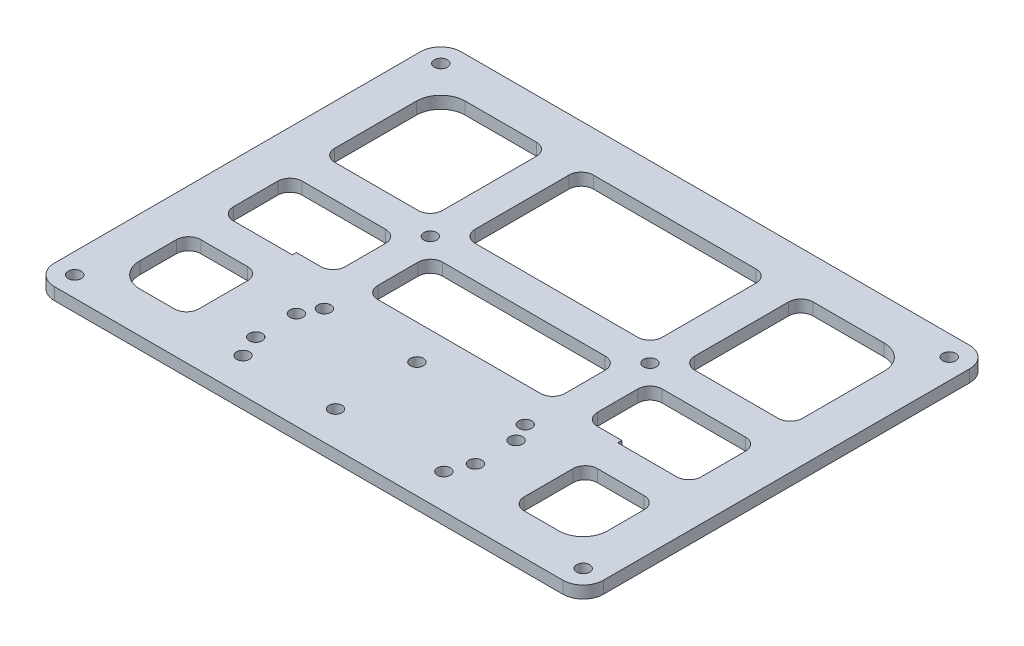
SolidWorks part; units mm, degrees
ref_plane "前视基准面" through (0, 0, 0) normal (0, 0, 1) x (1, 0, 0)
ref_plane "上视基准面" through (0, 0, 0) normal (0, 1, 0) x (1, 0, 0)
ref_plane "右视基准面" through (0, 0, 0) normal (1, 0, 0) x (0, 0, -1)
other "Configuration Table"
sketch "草图1" plane through (0, 0, 0) normal (0, 1, 0) x (1, 0, 0)
  line L1 (-62.5, 50) -> (62.5, 50)
  line L2 (-67.5, 45) -> (-67.5, -45)
  line L3 (-62.5, -50) -> (62.5, -50)
  line L4 (67.5, 45) -> (67.5, -45)
  line L5 (-67.5, 50) -> (67.5, -50) construction
  line L6 (-67.5, -50) -> (67.5, 50) construction
  line L7 (-62.5, 45) -> (62.5, 45) construction
  line L8 (-62.5, 45) -> (-62.5, -45) construction
  line L9 (-62.5, -45) -> (62.5, -45) construction
  line L10 (62.5, 45) -> (62.5, -45) construction
  line L11 (-62.5, 45) -> (62.5, -45) construction
  line L12 (-62.5, -45) -> (62.5, 45) construction
  circle A0 centre (-62.5, 45) radius 1.6
  circle A1 centre (62.5, 45) radius 1.6
  circle A2 centre (-62.5, -45) radius 1.6
  circle A3 centre (62.5, -45) radius 1.6
  arc A4 (67.5, 45) -> (62.5, 50) centre (62.5, 45) ccw
  arc A5 (62.5, -50) -> (67.5, -45) centre (62.5, -45) ccw
  arc A6 (-62.5, -50) -> (-67.5, -45) centre (-62.5, -45) cw
  arc A7 (-67.5, 45) -> (-62.5, 50) centre (-62.5, 45) cw
  point P0 (0, 0)
  point P6 (0, 0)
  dimension "D5" = 3.2
  dimension "D6" = 3.2
  dimension "D7" = 3.2
  dimension "D8" = 3.2
  dimension "D9" = 5
  dimension "D1" = 100
  dimension "D2" = 135
  dimension "D3" = 125
  dimension "D4" = 90
extrude "凸台-拉伸1" add sketch "草图1" along normal blind 3
sketch "草图2" plane through (0, 3, 0) normal (0, 1, 0) x (1, 0, 0)
  line L0 (-40, -50) -> (-36, -50) construction
  line L1 (-36, -50) -> (9.5, -50) construction
  line L2 (9.5, -50) -> (13.5, -50) construction
  line L3 (13.5, -50) -> (36, -50) construction
  line L4 (36, -50) -> (40, -50) construction
  line L5 (40, -50) -> (40, -13) construction
  line L6 (40, -13) -> (36, -13) construction
  line L7 (36, -13) -> (13.5, -13) construction
  line L8 (13.5, -13) -> (9.5, -13) construction
  line L9 (9.5, -13) -> (-36, -13) construction
  line L10 (-36, -13) -> (-40, -13) construction
  line L11 (-40, -13) -> (-40, -50) construction
  line L12 (-40, -50) -> (-40, -30.5685)
  line L13 (-62.5, -50) -> (62.5, -50) construction
  line L14 (-67.5, 45) -> (-67.5, -45) construction
  circle A0 centre (-24.625, -21.5) radius 1.6
  circle A1 centre (24.75, -41.5) radius 1.6
  circle A2 centre (-24.625, -41.5) radius 1.6
  circle A3 centre (-1.875, -21.5) radius 1.6
  circle A4 centre (-1.875, -41.5) radius 1.6
  circle A5 centre (24.75, -21.5) radius 1.6
  dimension "D1" = 27.5
extrude "切除-拉伸1" cut sketch "草图2" against normal through all contours A2 | A0 | A4 | A3 | A1 | A5
sketch "草图3" plane through (0, 3, 0) normal (0, 1, 0) x (1, 0, 0)
  line L0 (0, 59.9845) -> (0, -64.6631) construction
  line L1 (-62.5, -50) -> (62.5, -50) construction
  circle A0 centre (-27, -36) radius 1.6
  circle A1 centre (27, -36) radius 1.6
  circle A2 centre (-27, 6.92) radius 1.6
  circle A3 centre (27, 6.92) radius 1.6
  circle A4 centre (-27, -26) radius 1.6
  circle A5 centre (27, -26) radius 1.6
  dimension "D1" = 3.2
  dimension "D4" = 3.2
  dimension "D7" = 3.2
  dimension "D2" = 54
  dimension "D3" = 14
  dimension "D5" = 54
  dimension "D6" = 42.92
  dimension "D8" = 10
  dimension "D9" = 54
extrude "切除-拉伸2" cut sketch "草图3" against normal through all
sketch "草图6" plane through (0, 3, 0) normal (0, 1, 0) x (1, 0, 0)
  line L0 (-57.5, -18) -> (40, -18) construction
  line L1 (-57.5, 6.92) -> (-31, 6.92)
  line L2 (27, 40) -> (27, 10.92)
  line L3 (-27, 40) -> (-27, 10.92)
  line L4 (-40, -18) -> (40, -18) construction
  line L5 (-57.5, -18) -> (57.5, -18)
  line L6 (-54.5, -22) -> (-43, -22)
  line L7 (23, 37) -> (23, 13.92)
  line L8 (-40, -50) -> (-40, -30.5685) construction
  line L9 (-40, -37) -> (-40, -30.5685)
  line L10 (-31, 37) -> (-31, 13.92)
  line L11 (-40, -50) -> (40, -50)
  line L12 (57.5, 40) -> (-57.5, 40)
  line L13 (-57.5, 40) -> (-57.5, -40)
  line L14 (-57.5, -40) -> (57.5, -40)
  line L15 (57.5, -40) -> (57.5, 40)
  line L16 (51.5, 40) -> (34, 40)
  line L17 (-57.5, 34) -> (-57.5, 13.92)
  line L18 (-51.5, -40) -> (-43, -40)
  line L19 (57.5, -34) -> (57.5, -25)
  line L20 (-40, -40) -> (-40, -25)
  line L21 (-40, -13) -> (-34, -13)
  line L22 (40, -37) -> (40, -25)
  line L23 (-54.5, 2.92) -> (-34, 2.92)
  line L24 (-54.5, -14) -> (-40, -14)
  line L25 (31, 37) -> (31, 13.92)
  line L26 (-23, 37) -> (-23, 13.92)
  line L27 (-54.5, 10.92) -> (-34, 10.92)
  line L28 (34, 10.92) -> (54.5, 10.92)
  line L29 (-57.5, 10.92) -> (57.5, 10.92) construction
  line L30 (25.4, 6.92) -> (28.6, 6.92)
  line L31 (-57.5, 6.92) -> (57.5, 6.92) construction
  line L32 (34, 2.92) -> (54.5, 2.92)
  line L33 (-57.5, 2.92) -> (57.5, 2.92) construction
  line L34 (27, 8.52) -> (27, 5.32)
  line L35 (27, 40) -> (27, -13) construction
  line L36 (31, 6.92) -> (57.5, 6.92)
  line L37 (27, 2.92) -> (27, -13)
  line L38 (31, -0.08) -> (31, -10)
  line L39 (31, 40) -> (31, -13) construction
  line L40 (23, -0.08) -> (23, -10)
  line L41 (23, 40) -> (23, -13) construction
  line L42 (-28.6, 6.92) -> (-25.4, 6.92)
  line L43 (-27, 2.92) -> (-27, -13)
  line L44 (-27, 40) -> (-27, -13) construction
  line L45 (-23, 6.92) -> (23, 6.92)
  line L46 (-27, 8.52) -> (-27, 5.32)
  line L47 (-20, 10.92) -> (20, 10.92)
  line L48 (-23, -0.08) -> (-23, -10)
  line L49 (-23, 40) -> (-23, -13) construction
  line L50 (-20, 2.92) -> (20, 2.92)
  line L51 (-31, -0.08) -> (-31, -10)
  line L52 (-31, 40) -> (-31, -13) construction
  line L53 (-57.5, -25) -> (-57.5, -34)
  line L54 (-40, -14) -> (-40, -13)
  line L55 (40, -14) -> (40, -13)
  line L56 (57.5, -11) -> (57.5, -0.08)
  line L57 (-26.1449, -22) -> (26.2699, -22)
  line L58 (-57.5, -22) -> (57.5, -22) construction
  line L59 (43, -22) -> (54.5, -22)
  line L60 (43, -40) -> (51.5, -40)
  line L61 (-25.1818, -40) -> (25.3068, -40)
  line L62 (-57.5, -0.08) -> (-57.5, -11)
  line L63 (-34, 40) -> (-51.5, 40)
  line L64 (20, 40) -> (-20, 40)
  line L65 (57.5, 13.92) -> (57.5, 34)
  line L66 (34, -13) -> (40, -13)
  line L67 (-40, -13) -> (40, -13) construction
  line L68 (40, -14) -> (54.5, -14)
  line L69 (-57.5, -14) -> (57.5, -14) construction
  line L70 (-20, -13) -> (20, -13)
  circle A0 centre (27, 6.92) radius 1.6 construction
  circle A1 centre (-27, 6.92) radius 1.6 construction
  circle A2 centre (27, 6.92) radius 1.6
  circle A3 centre (-27, 6.92) radius 1.6
  arc A4 (-43, -40) -> (-40, -37) centre (-43, -37) ccw
  arc A5 (-43, -22) -> (-40, -25) centre (-43, -25) cw
  arc A6 (-57.5, -25) -> (-54.5, -22) centre (-54.5, -25) cw
  arc A7 (43, -40) -> (40, -37) centre (43, -37) cw
  arc A8 (51.5, -40) -> (57.5, -34) centre (51.5, -34) ccw
  arc A9 (57.5, 34) -> (51.5, 40) centre (51.5, 34) ccw
  arc A10 (-51.5, -40) -> (-57.5, -34) centre (-51.5, -34) cw
  arc A11 (-57.5, 34) -> (-51.5, 40) centre (-51.5, 34) cw
  arc A12 (40, -25) -> (43, -22) centre (43, -25) cw
  circle A13 centre (24.75, -41.5) radius 1.6
  circle A14 centre (24.75, -41.5) radius 1.6
  circle A15 centre (-24.625, -21.5) radius 1.6
  circle A16 centre (-24.625, -21.5) radius 1.6
  circle A17 centre (24.75, -21.5) radius 1.6
  circle A18 centre (24.75, -21.5) radius 1.6
  circle A19 centre (-1.875, -41.5) radius 1.6
  circle A20 centre (-1.875, -41.5) radius 1.6
  circle A21 centre (-1.875, -21.5) radius 1.6
  circle A22 centre (-1.875, -21.5) radius 1.6
  circle A23 centre (-24.625, -41.5) radius 1.6
  circle A24 centre (-24.625, -41.5) radius 1.6
  arc A25 (57.5, -25) -> (54.5, -22) centre (54.5, -25) ccw
  arc A26 (57.5, -11) -> (54.5, -14) centre (54.5, -11) cw
  arc A27 (34, -13) -> (31, -10) centre (34, -10) cw
  arc A28 (31, -0.08) -> (34, 2.92) centre (34, -0.08) cw
  arc A29 (57.5, -0.08) -> (54.5, 2.92) centre (54.5, -0.08) ccw
  arc A30 (54.5, 10.92) -> (57.5, 13.92) centre (54.5, 13.92) ccw
  arc A31 (31, 13.92) -> (34, 10.92) centre (34, 13.92) ccw
  arc A32 (31, 37) -> (34, 40) centre (34, 37) cw
  arc A33 (20, 10.92) -> (23, 13.92) centre (20, 13.92) ccw
  arc A34 (23, 37) -> (20, 40) centre (20, 37) ccw
  arc A35 (-23, 37) -> (-20, 40) centre (-20, 37) cw
  arc A36 (-20, 10.92) -> (-23, 13.92) centre (-20, 13.92) cw
  arc A37 (20, -13) -> (23, -10) centre (20, -10) ccw
  arc A38 (23, -0.08) -> (20, 2.92) centre (20, -0.08) ccw
  arc A39 (-20, -13) -> (-23, -10) centre (-20, -10) cw
  arc A40 (-23, -0.08) -> (-20, 2.92) centre (-20, -0.08) cw
  arc A41 (-34, -13) -> (-31, -10) centre (-34, -10) ccw
  arc A42 (-54.5, -14) -> (-57.5, -11) centre (-54.5, -11) cw
  arc A43 (-54.5, 2.92) -> (-57.5, -0.08) centre (-54.5, -0.08) ccw
  arc A44 (-31, -0.08) -> (-34, 2.92) centre (-34, -0.08) ccw
  arc A45 (-34, 10.92) -> (-31, 13.92) centre (-34, 13.92) ccw
  arc A46 (-34, 40) -> (-31, 37) centre (-34, 37) cw
  arc A47 (-54.5, 10.92) -> (-57.5, 13.92) centre (-54.5, 13.92) cw
  point P119 (40, -22)
  point P131 (31, 2.92)
  point P156 (23, 2.92)
  point P162 (-23, 2.92)
  point P174 (-31, 2.92)
  dimension "D2" = 6
  dimension "D15" = 3
  dimension "D9" = 80
  dimension "D10" = 37
  dimension "D11" = 5
  dimension "D12" = 4
  dimension "D14" = 115
  dimension "D1" = 10
  dimension "D3" = 0
  dimension "D4" = 0
  dimension "D5" = 0
  dimension "D6" = 0
  dimension "D7" = 0
  dimension "D8" = 0
  dimension "D13" = 4
extrude "切除-拉伸3" cut sketch "草图6" against normal through all and the other way through all contours A47 L27 A45 L10 A46 L63 A11 L17 | A36 L47 A33 L7 A34 L64 A35 L26 | A32 L25 A31 L28 A30 L65 A9 L16 | L56 A29 L32 A28 L38 A27 L66 L55 L68 A26 | A40 L48 A39 L70 A37 L40 A38 L50 | L51 A44 L23 A43 L62 A42 L24 L54 L21 A41 | A10 L18 A4 L9 L20 A5 L6 A6 L53 | L19 A25 L59 A12 L22 A7 L60 A8
